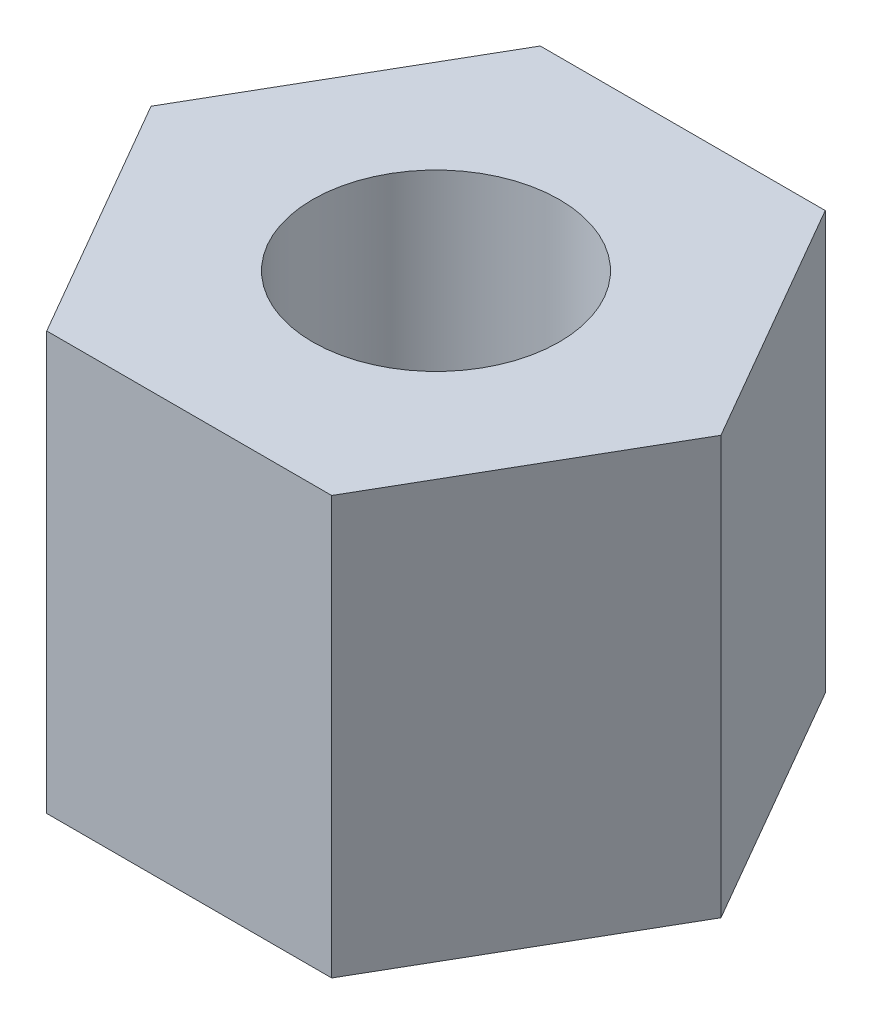
SolidWorks part; units mm, degrees
ref_plane "Front Plane" through (0, 0, 0) normal (0, 0, 1) x (1, 0, 0)
ref_plane "Top Plane" through (0, 0, 0) normal (0, 1, 0) x (1, 0, 0)
ref_plane "Right Plane" through (0, 0, 0) normal (1, 0, 0) x (0, 0, -1)
sketch "Sketch1" plane through (0, 0, 0) normal (0, 1, 0) x (1, 0, 0)
  line L0 (0, 0) -> (0, 3.0408) construction
  line L1 (-1.7321, -3) -> (1.7321, -3)
  line L2 (1.7321, -3) -> (3.4641, 0)
  line L3 (3.4641, 0) -> (1.7321, 3)
  line L4 (1.7321, 3) -> (-1.7321, 3)
  line L5 (-1.7321, 3) -> (-3.4641, 0)
  line L6 (-3.4641, 0) -> (-1.7321, -3)
  circle A0 centre (0, 0) radius 3 construction
  circle A1 centre (0, 0) radius 1.5
  dimension "D1" = 6
  dimension "D2" = 3
extrude "Boss-Extrude1" add sketch "Sketch1" along normal mid plane 5.08
